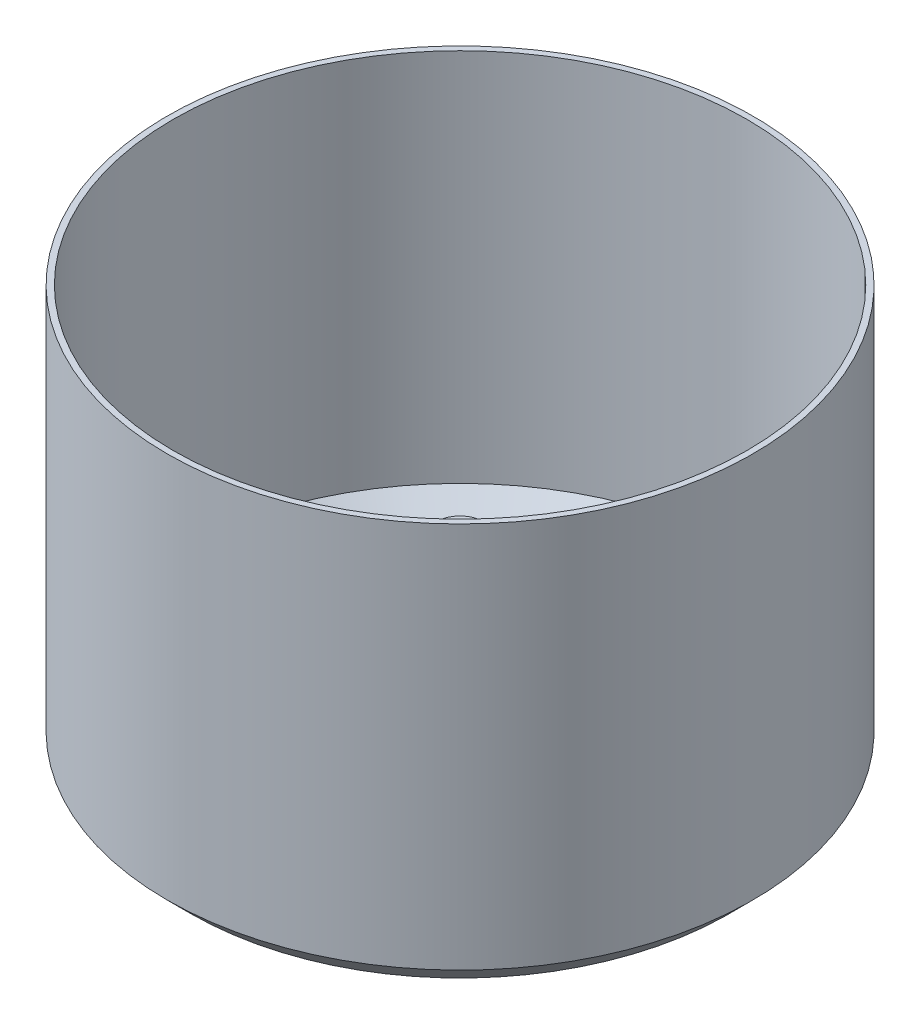
SolidWorks part; units mm, degrees
material "ABS"
ref_plane "Front Plane" through (0, 0, 0) normal (0, 0, 1) x (1, 0, 0)
ref_plane "Top Plane" through (0, 0, 0) normal (0, 1, 0) x (1, 0, 0)
ref_plane "Right Plane" through (0, 0, 0) normal (1, 0, 0) x (0, 0, -1)
sketch "Sketch1" plane through (0, 0, 0) normal (0, 1, 0) x (1, 0, 0)
  circle A0 centre (0, 0) radius 50
  circle A1 centre (0, 0) radius 49
  dimension "D1" = 100
  dimension "D2" = 1
extrude "Main Wall" add sketch "Sketch1" along normal blind 70
sketch "Sketch2" plane through (0, 0, 0) normal (0, -1, 0) x (1, 0, 0)
  circle A1 centre (0, 0) radius 50
  circle A2 centre (0, 0) radius 50
  dimension "D1" = 0
extrude "Floor" add sketch "Sketch2" against normal blind 2
chamfer "Inner Floor Chamfer" distance 4 angle 45 1 edges at (0, 2, -49)
chamfer "Outer Floor Chamfer" distance 4 angle 45 1 edges at (0, 0, 50)
sketch "Sketch3" plane through (0, 2, 0) normal (0, 1, 0) x (1, 0, 0)
  circle A0 centre (-21, 21) radius 5
  circle A1 centre (21, 21) radius 5
  circle A2 centre (21, -21) radius 5
  circle A3 centre (-21, -21) radius 5
  point P12 (0, 0)
  dimension "D3" = 10
  dimension "D1" = 21
  dimension "D2" = 21
  dimension "D4" = 4
extrude "Connector Peg" add sketch "Sketch3" along normal blind 10
chamfer "Peg Chamfer" distance 1 angle 45 4 edges at (-21, 12, 26) (21, 12, 26) (21, 12, -16) (-21, 12, -16)
chamfer "Chamfer1" distance 1 angle 45 4 edges at (21, 2, 16) (21, 2, -26) (-21, 2, 16) (-21, 2, -26)
